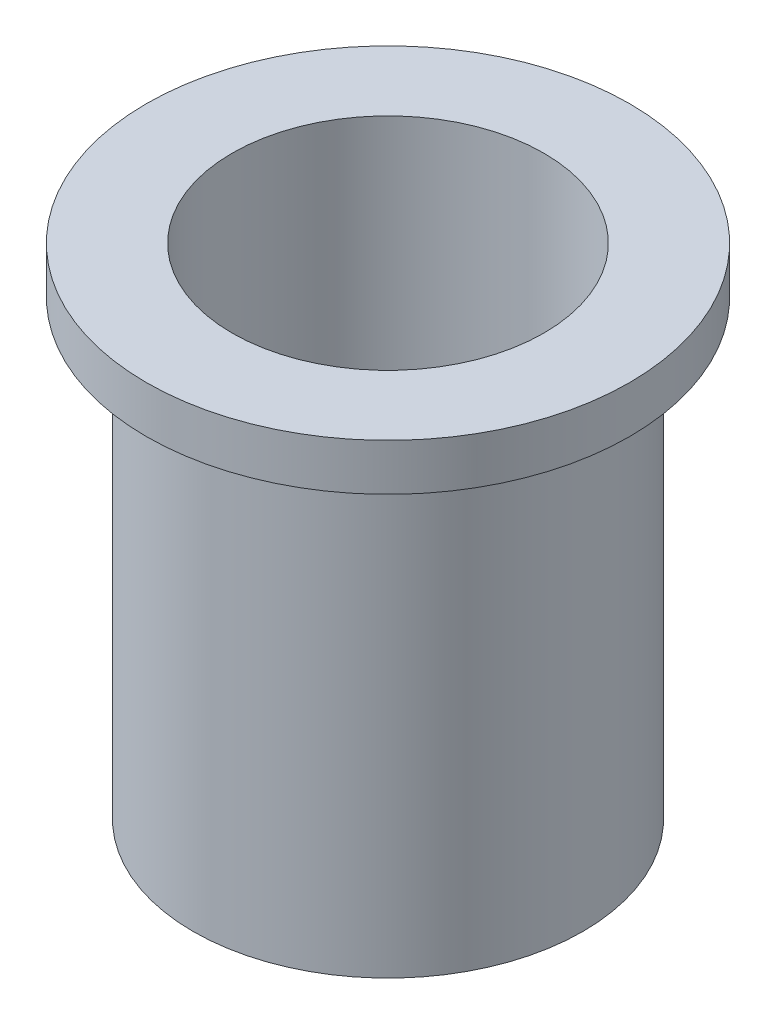
SolidWorks part; units mm, degrees
ref_plane "Front Plane" through (0, 0, 0) normal (0, 0, 1) x (1, 0, 0)
ref_plane "Top Plane" through (0, 0, 0) normal (0, 1, 0) x (1, 0, 0)
ref_plane "Right Plane" through (0, 0, 0) normal (1, 0, 0) x (0, 0, -1)
sketch "Sketch1" plane through (0, 0, 0) normal (0, 0, 1) x (1, 0, 0)
  line L0 (20, 0) -> (20, 64)
  line L1 (20, 64) -> (31, 64)
  line L2 (31, 64) -> (31, 58)
  line L3 (31, 58) -> (25, 58)
  line L4 (25, 58) -> (25, 0)
  line L5 (25, 0) -> (20, 0)
  line L6 (0, 0) -> (0, 110.2857) construction
  dimension "D1" = 20
  dimension "D2" = 25
  dimension "D3" = 31
  dimension "D4" = 64
  dimension "D5" = 6
revolve "Revolve1" add sketch "Sketch1" angle 360 about L6
